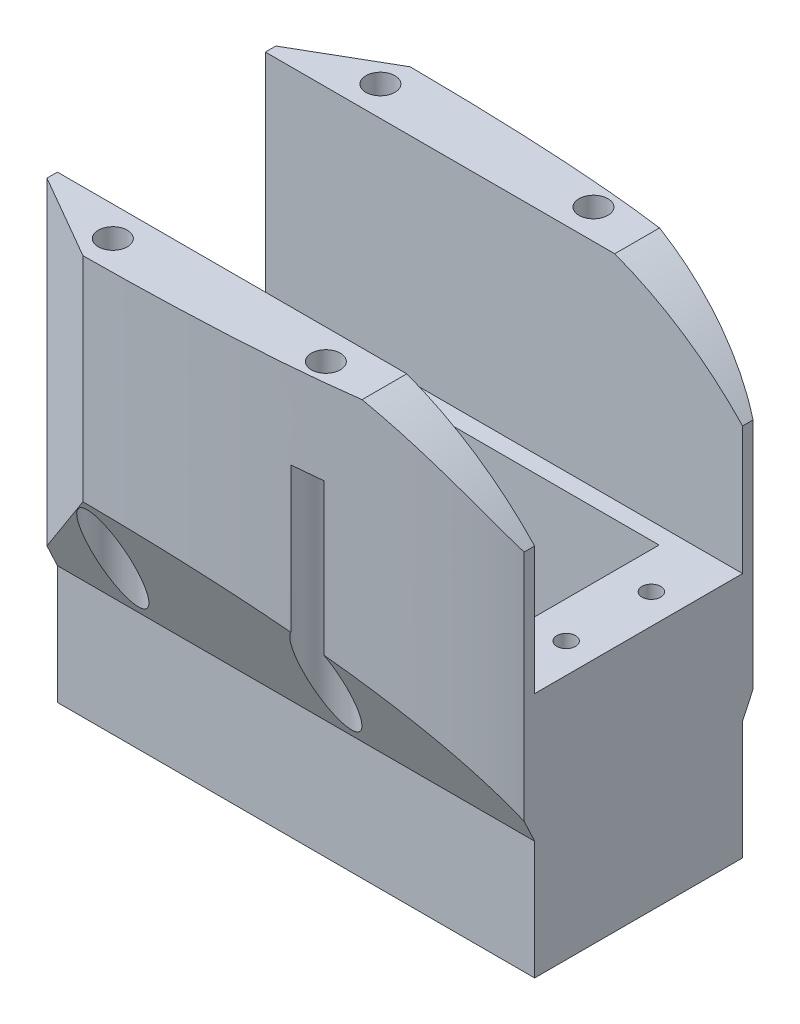
SolidWorks part; units mm, degrees
ref_plane "Front Plane" through (0, 0, 0) normal (0, 0, 1) x (1, 0, 0)
ref_plane "Top Plane" through (0, 0, 0) normal (0, 1, 0) x (1, 0, 0)
ref_plane "Right Plane" through (0, 0, 0) normal (1, 0, 0) x (0, 0, -1)
sketch "Sketch1" plane through (0, 0, 0) normal (0, 1, 0) x (1, 0, 0)
  line L1 (0, 0) -> (40.4, 0)
  line L2 (0, 0) -> (0, 20.4)
  line L3 (0, 20.4) -> (40.4, 20.4)
  line L4 (40.4, 0) -> (40.4, 20.4)
  line L9 (-7.8, 22.4) -> (48.2, 22.4)
  line L10 (-7.8, 22.4) -> (-7.8, -2)
  line L11 (-7.8, -2) -> (48.2, -2)
  line L12 (48.2, 22.4) -> (48.2, -2)
  point P9 (20.2, 0)
  point P10 (20.2, -2)
  point P11 (48.2, 10.2)
  point P12 (40.4, 10.2)
  dimension "D1" = 40.4
  dimension "D2" = 20.4
  dimension "D3" = 2
  dimension "D4" = 56
extrude "Boss-Extrude1" add sketch "Sketch1" along normal blind 27.9
sketch "Sketch2" plane through (0, 0, 0) normal (0, -1, 0) x (-1, 0, 0)
  line L1 (7.8, -2) -> (-48.2, -2)
  line L2 (7.8, -2) -> (7.8, 22.4)
  line L3 (7.8, 22.4) -> (-48.2, 22.4)
  line L4 (-48.2, -2) -> (-48.2, 22.4)
extrude "Boss-Extrude2" add sketch "Sketch2" along normal blind 1
sketch "Sketch3" plane through (48.2, 0, 0) normal (1, 0, 0) x (0, 0, -1)
  line L0 (22.4, 12.9) -> (29.4, 27.9)
  line L1 (22.4, 27.9) -> (22.4, -1) construction
  line L2 (29.4, 27.9) -> (29.4, 52.9)
  line L3 (29.4, 52.9) -> (22.4, 52.9)
  line L4 (22.4, 52.9) -> (22.4, 12.9)
  line L5 (-2, 27.9) -> (22.4, 27.9) construction
  dimension "D1" = 25
  dimension "D2" = 15
  dimension "D3" = 25
  dimension "D4" = 7
extrude "Boss-Extrude3" add sketch "Sketch3" against normal up to surface (56 mm away) up to face at (-7.8, 13.45, -10.2)
ref_plane "Plane1" through (0, 0, -10.2) normal (0, 0, 1) x (1, 0, 0)
sketch "Sketch4" plane through (0, 52.9, 0) normal (0, 1, 0) x (1, 0, 0)
  line L0 (48.2, 22.4) -> (-7.8, 22.4) construction
  line L1 (-7.8, 22.4) -> (-7.8, 29.4) construction
  circle A0 centre (2.2, 25.9) radius 1.7
  circle A1 centre (27.2, 25.9) radius 1.7
  dimension "D1" = 3.4
  dimension "D3" = 25
  dimension "D4" = 10
  dimension "D2" = 3.5
extrude "Cut-Extrude1" cut sketch "Sketch4" against normal through all
sketch "Sketch5" plane through (0, 52.9, 0) normal (0, 1, 0) x (1, 0, 0)
  circle A0 centre (2.2, 25.9) radius 3
  circle A1 centre (27.2, 25.9) radius 3
  dimension "D1" = 6
extrude "Cut-Extrude2" cut sketch "Sketch5" against normal through all from offset 10 offset against normal yes
mirror "Mirror1" about plane through (0, 0, -10.2) normal (0, 0, 1) of "Cut-Extrude2", "Cut-Extrude1", "Boss-Extrude3"
chamfer "Chamfer1" distance 10 angle 30 1 edges at (-7.8, 40.4, -29.4)
chamfer "Chamfer2" distance 10 angle 30 1 edges at (48.2, 40.4, -29.4)
chamfer "Chamfer3" distance 10 angle 30 1 edges at (-7.8, 40.4, 9)
chamfer "Chamfer4" distance 10 angle 30 1 edges at (48.2, 40.4, 9)
sketch "Sketch6" plane through (0, 27.9, 0) normal (0, 1, 0) x (1, 0, 0)
  line L0 (-7.8, 22.4) -> (-7.8, -2) construction
  line L1 (-7.8, 13.2) -> (0, 13.2)
  line L2 (-7.8, 13.2) -> (-7.8, 7.2)
  line L3 (-7.8, 7.2) -> (0, 7.2)
  line L4 (0, 13.2) -> (0, 7.2)
  line L5 (0, 20.4) -> (0, 0) construction
  line L6 (-7.645, 10.2) -> (7.645, 10.2) construction
  point P8 (0, 10.2)
  dimension "D1" = 6
extrude "Cut-Extrude3" cut sketch "Sketch6" against normal up to surface (27.9 mm away) up to face at (20.2, 0, -10.2)
sketch "Sketch7" plane through (0, 27.9, 0) normal (0, 1, 0) x (1, 0, 0)
  line L0 (44.7, 15.2) -> (44.7, 5.2) construction
  line L1 (-7.645, 10.2) -> (7.645, 10.2) construction
  line L2 (-4.3, 15.2) -> (44.7, 15.2) construction
  line L3 (40.4, 20.4) -> (0, 20.4) construction
  circle A0 centre (-4.3, 15.2) radius 1.1
  circle A1 centre (-4.3, 5.2) radius 1.1
  circle A2 centre (44.7, 15.2) radius 1.1
  circle A3 centre (44.7, 5.2) radius 1.1
  point P8 (44.7, 10.2)
  point P13 (20.2, 20.4)
  point P14 (20.2, 15.2)
  dimension "D1" = 2.2
  dimension "D2" = 49
  dimension "D3" = 10
extrude "Cut-Extrude4" cut sketch "Sketch7" against normal blind 30
sketch "Sketch8" plane through (0, 52.9, 0) normal (0, 1, 0) x (1, 0, 0)
  line L0 (48.2, 23.6265) -> (38.2, 29.4) construction
  line L1 (55.8011, 19.238) -> (40.5812, 28.0252) construction
  spline S0 degree 2 poles (2.2, 29.4) (38.6876, 29.1185) (48.2, 23.6265) knots 0 0 0 1 1 1
  line M5 (48.2, 23.6265) -> (38.2, 29.4)
  line M6 (38.2, 29.4) -> (2.2, 29.4)
extrude "Cut-Extrude5" cut sketch "Sketch8" against normal through all and the other way through all contours S0 M6 M5
mirror "Mirror2" about plane through (0, 0, -10.2) normal (0, 0, 1) of "Cut-Extrude5"
sketch "Sketch9" plane through (0, 0, 2) normal (0, 0, 1) x (1, 0, 0)
  line L1 (48.2, 52.9) -> (48.2, 15.5282) construction
  line L2 (33.2, 52.9) -> (48.2, 52.9)
  line L3 (48.2, 52.9) -> (48.2, 42.9)
  line L4 (48.2, 52.9) -> (2.2, 52.9) construction
  arc A0 (33.2, 52.9) -> (48.2, 42.9) centre (19.0827, 15.474) cw
  point P3 (30.0247, 52.9)
  dimension "D2" = 40
  dimension "D1" = 10
  dimension "D3" = 15
extrude "Cut-Extrude6" cut sketch "Sketch9" against normal through all and the other way through all
